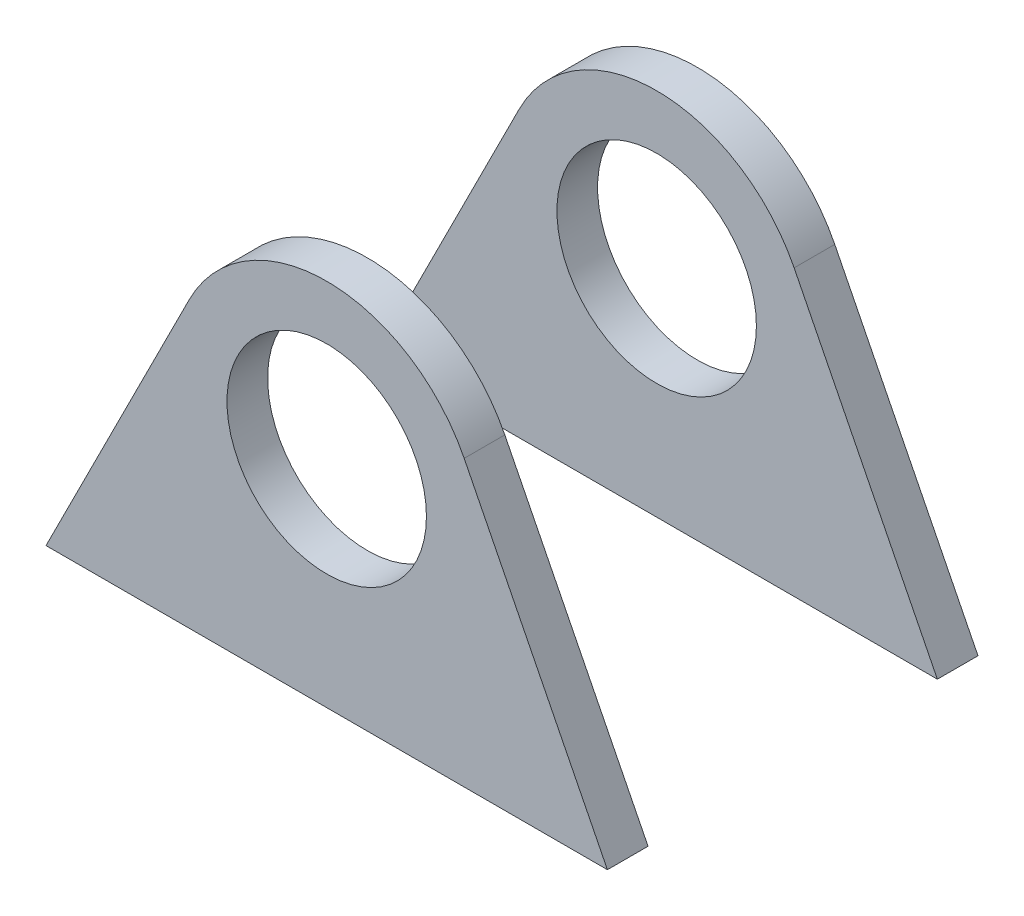
SolidWorks part; units mm, degrees
ref_plane "Front Plane" through (0, 0, 0) normal (0, 0, 1) x (1, 0, 0)
ref_plane "Top Plane" through (0, 0, 0) normal (0, 1, 0) x (1, 0, 0)
ref_plane "Right Plane" through (0, 0, 0) normal (1, 0, 0) x (0, 0, -1)
sketch "Sketch1" plane through (0, 0, 0) normal (0, 0, 1) x (1, 0, 0)
  line L0 (-22.8, -17.5) -> (22.8, -17.5)
  line L1 (-22.8, -17.5) -> (-11.1659, 5.619)
  line L2 (0, -17.5) -> (0, 34.4426) construction
  line L3 (22.8, -17.5) -> (11.1659, 5.619)
  circle A0 centre (0, 0) radius 8.1
  arc A1 (-11.1659, 5.619) -> (11.1659, 5.619) centre (0, 0) cw
  point P6 (0, -17.5)
  point P19 (0, 12.5)
  dimension "D1" = 16.2
  dimension "D3" = 30
  dimension "D4" = 12.5
  dimension "D2" = 45.6
extrude "Boss-Extrude1" add sketch "Sketch1" along normal blind 3.3
sketch "Sketch2" plane through (0, 0, 0) normal (0, 1, 0) x (1, 0, 0)
  line L0 (0, -3.3) -> (0, -26.8) construction
  line L1 (-11.1659, -3.3) -> (11.1659, -3.3) construction
  dimension "D1" = 23.5
ref_point "Point1"
ref_plane "Plane1" through (0, 0, 15.05) normal (0, 0, 1) x (1, 0, 0)
mirror "Mirror6" about plane through (0, 0, 15.05) normal (0, 0, 1) of bodies 101
